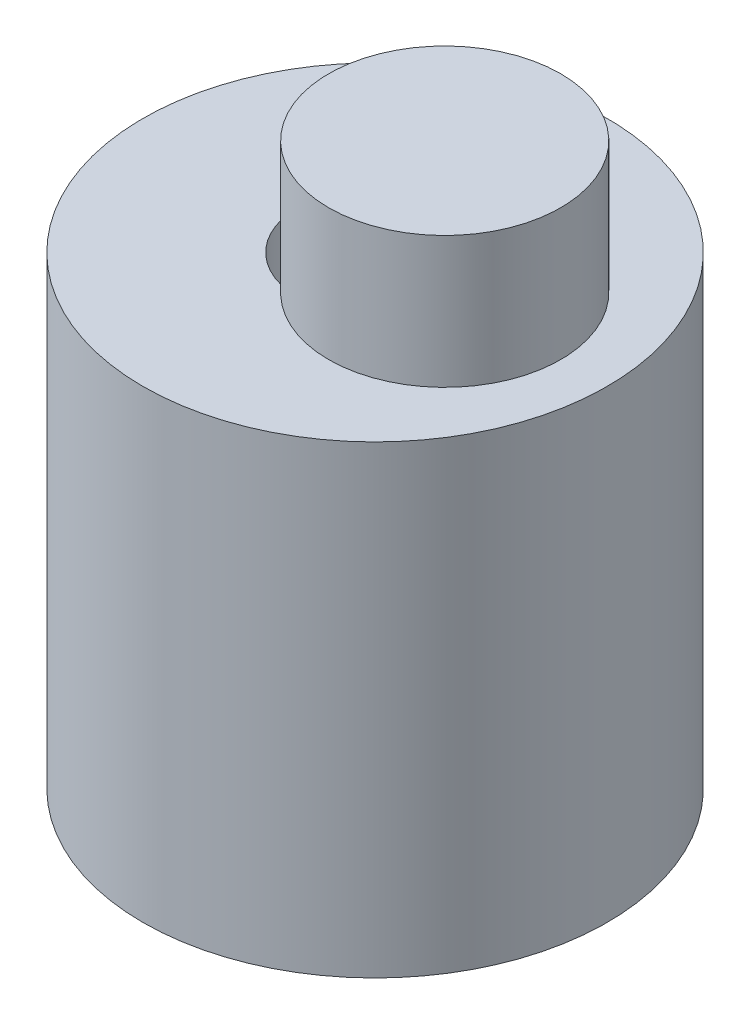
SolidWorks part; units mm, degrees
ref_plane "Front Plane" through (0, 0, 0) normal (0, 0, 1) x (1, 0, 0)
ref_plane "Top Plane" through (0, 0, 0) normal (0, 1, 0) x (1, 0, 0)
ref_plane "Right Plane" through (0, 0, 0) normal (1, 0, 0) x (0, 0, -1)
sketch "Sketch1" plane through (0, 0, 0) normal (0, 1, 0) x (1, 0, 0)
  circle A0 centre (0, 0) radius 3
  circle A1 centre (0, 0) radius 1
  dimension "D1" = 2
  dimension "D2" = 6
extrude "Boss-Extrude1" add sketch "Sketch1" along normal blind 6
sketch "Sketch2" plane through (0, 6, 0) normal (0, 1, 0) x (1, 0, 0)
  line L0 (0, 0) -> (0.9, 0) construction
  circle A0 centre (0.9, 0) radius 1.5
  dimension "D1" = 3
  dimension "D2" = 0.9
extrude "Boss-Extrude2" add sketch "Sketch2" along normal blind 1.7
